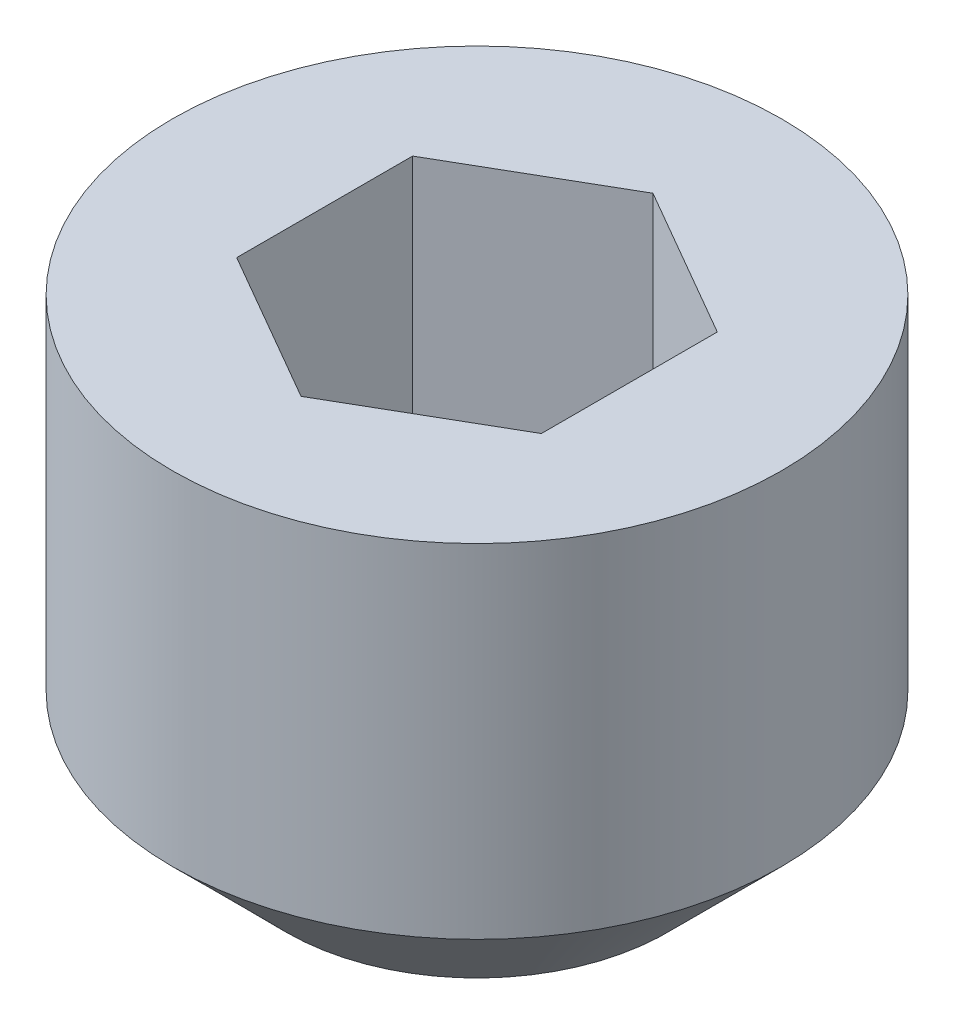
SolidWorks part; units mm, degrees
ref_plane "Front Plane" through (0, 0, 0) normal (0, 0, 1) x (1, 0, 0)
ref_plane "Top Plane" through (0, 0, 0) normal (0, 1, 0) x (1, 0, 0)
ref_plane "Right Plane" through (0, 0, 0) normal (1, 0, 0) x (0, 0, -1)
sketch "Sketch1" plane through (0, 0, 0) normal (0, 0, 1) x (1, 0, 0)
  line L0 (0, 3) -> (0, 0) construction
  line L1 (0, 3) -> (2, 3)
  line L2 (2, 3) -> (2, 0)
  line L3 (2, 0) -> (0, 0)
  line L4 (0, 3) -> (0, 0)
  dimension "SS_M" = 4
  dimension "SS_L" = 3
revolve "Revolve1" add sketch "Sketch1" angle 360 about L0
cosmetic thread "Cosmetic Thread1" parameters "SS_D1_s"=3.242
sketch "Sketch2" plane through (0, 0, 0) normal (0, 0, 1) x (1, 0, 0)
  line L0 (0, 3) -> (0, 0.9226) construction
  line L1 (0, 3) -> (1, 3)
  line L2 (1, 3) -> (1, 1.5)
  line L3 (1, 1.5) -> (0, 0.9226)
  line L4 (0, 3) -> (0, 0.9226)
  line L5 (2, 3) -> (-2, 3) construction
  dimension "D2" = 60
  dimension "SS_C" = 1.5
  dimension "SS_B" = 2
revolve "Cut-Revolve1" cut sketch "Sketch2" angle 360 about L0
sketch "Sketch3" plane through (0, 3, 0) normal (0, 1, 0) x (1, 0, 0)
  line L1 (0, 1.1547) -> (-1, 0.5774)
  line L2 (-1, 0.5774) -> (-1, -0.5774)
  line L3 (-1, -0.5774) -> (0, -1.1547)
  line L4 (0, -1.1547) -> (1, -0.5774)
  line L5 (1, -0.5774) -> (1, 0.5774)
  line L6 (1, 0.5774) -> (0, 1.1547)
  circle A0 centre (0, 0) radius 1 construction
  circle A1 centre (0, 0) radius 1 construction
extrude "Cut-Extrude1" cut sketch "Sketch3" against normal blind 1.5
sketch "Sketch4" plane through (0, 0, 0) normal (0, 0, 1) x (1, 0, 0)
  line L0 (1.25, 0) -> (2, 0)
  line L1 (2, 0) -> (2, 0.75)
  line L2 (2, 0.75) -> (1.25, 0)
  line L4 (-2, 0) -> (2, 0) construction
  line L5 (0, 0) -> (0, 3) construction
  line L6 (2, 3) -> (-2, 3) construction
  dimension "D1" = 45
  dimension "SS_D_s" = 2.5
  dimension "SS_M" = 4
revolve "Cut-Revolve2" cut sketch "Sketch4" angle 360 about L5
